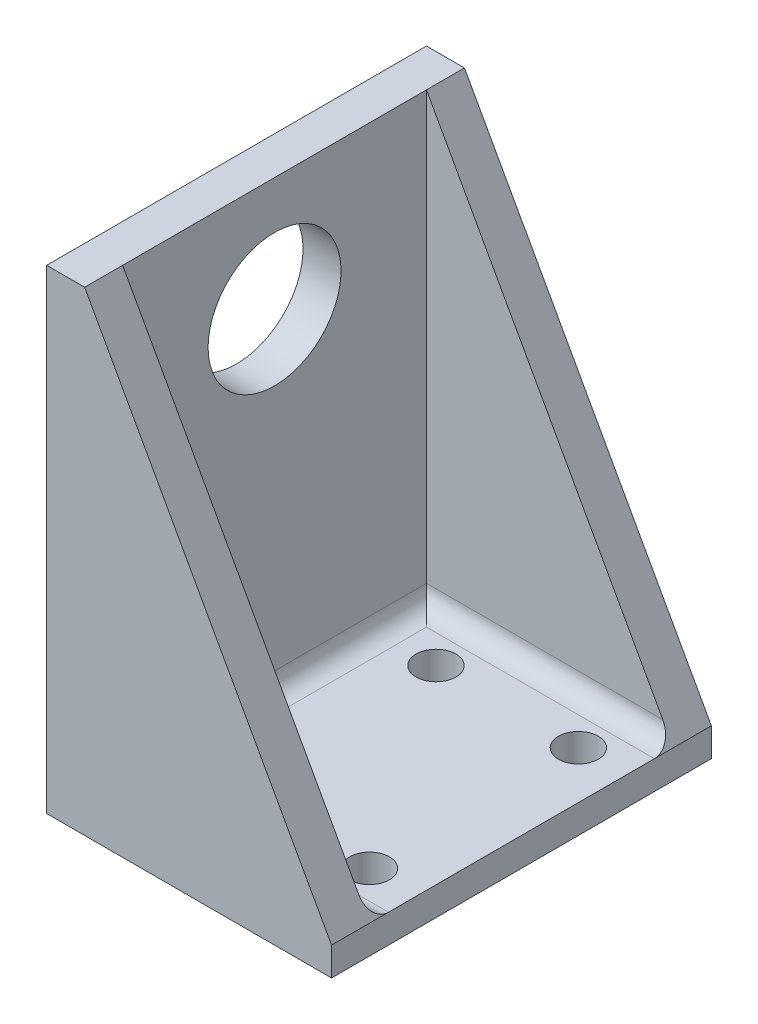
SolidWorks part; units mm, degrees
ref_plane "Front Plane" through (0, 0, 0) normal (0, 0, 1) x (1, 0, 0)
ref_plane "Top Plane" through (0, 0, 0) normal (0, 1, 0) x (1, 0, 0)
ref_plane "Right Plane" through (0, 0, 0) normal (1, 0, 0) x (0, 0, -1)
sketch "sss" plane through (0, 0, 0) normal (0, 1, 0) x (1, 0, 0)
  line L0 (-20, 0) -> (20, 0) construction
  line L1 (-10, -20) -> (20, -20)
  line L3 (-10, 20) -> (20, 20)
  line L4 (20, -20) -> (20, 20)
  line L5 (-20, -20) -> (20, 20) construction
  line L6 (-20, 20) -> (20, -20) construction
  line L7 (0, 19) -> (0, -21) construction
  line L8 (-10, 20) -> (-10, -20)
  line L9 (7.5, 20) -> (7.5, -20) construction
  circle A0 centre (0, 11) radius 2.1
  circle A3 centre (0, -11) radius 2.1
  circle A4 centre (15, -11) radius 2.1
  circle A5 centre (15, 11) radius 2.1
  point P0 (0, 0)
  dimension "D3" = 4.2
  dimension "D4" = 9
  dimension "D1" = 30
  dimension "D2" = 10
  dimension "D5" = 5
extrude "Boss-Extrude2" add sketch "sss" along normal blind 3
sketch "Sketch1" plane through (-10, 0, 0) normal (-1, 0, 0) x (0, 0, 1)
  line L1 (-20, 0) -> (20, 0)
  line L2 (-20, 0) -> (-20, 50)
  line L3 (-20, 50) -> (20, 50)
  line L4 (20, 0) -> (20, 50)
  circle A0 centre (0, 38) radius 7
  dimension "D2" = 14
  dimension "D1" = 50
  dimension "D3" = 12
extrude "Boss-Extrude3" add sketch "Sketch1" against normal blind 4
sketch "Sketch2" plane through (0, 0, 20) normal (0, 0, 1) x (1, 0, 0)
  line L0 (-10, 50) -> (-10, 0)
  line L1 (-10, 0) -> (20, 0) construction
  line L2 (-10, 50) -> (-10, 0) construction
  line L3 (-10, 0) -> (20, 0)
  line L4 (20, 0) -> (20, 3)
  line L5 (20, 3) -> (-6, 50)
  line L6 (-6, 50) -> (-10, 50)
extrude "Boss-Extrude4" add sketch "Sketch2" against normal blind 4
ref_plane "Plane1" through (0, 0, 0) normal (0, 0, 1) x (1, 0, 0)
mirror "Mirror1" about plane through (0, 0, 0) normal (0, 0, 1) of "Boss-Extrude4"
fillet "Fillet1" radius 2 3 edges at (7, 3, -16) (7, 3, 16) (-6, 3, 0)
equation "\"m4\"= 4.2"
equation "\"D3@sss\"=\"m4\""
